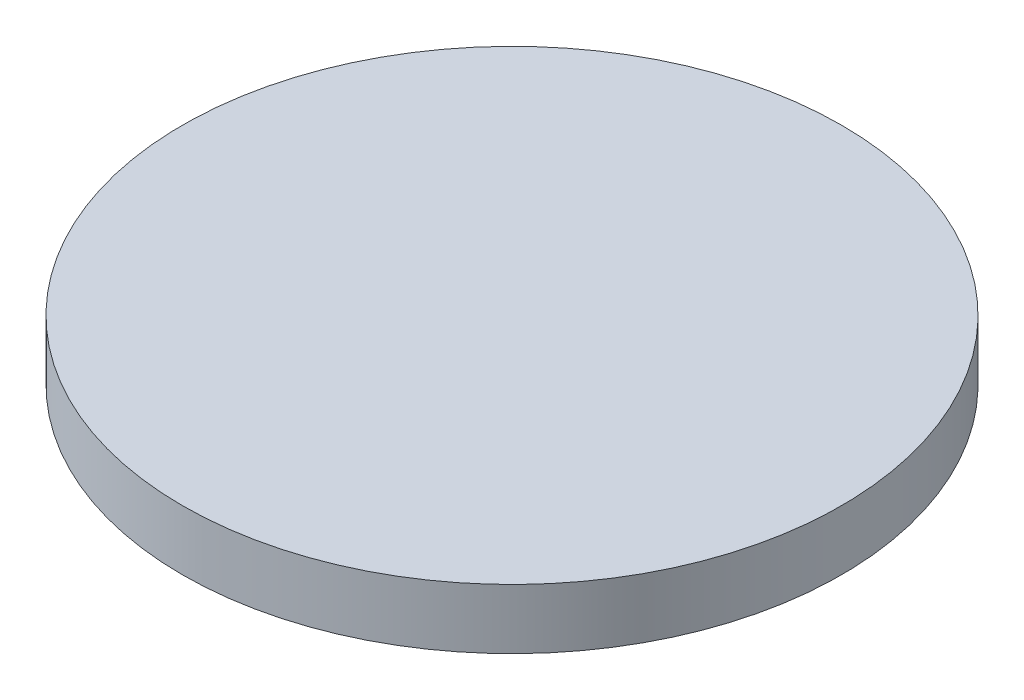
SolidWorks part; units mm, degrees
material "Natural Rubber"
ref_plane "Front Plane" through (0, 0, 0) normal (0, 0, 1) x (1, 0, 0)
ref_plane "Top Plane" through (0, 0, 0) normal (0, 1, 0) x (1, 0, 0)
ref_plane "Right Plane" through (0, 0, 0) normal (1, 0, 0) x (0, 0, -1)
sketch "BaseS" plane through (0, 0, 0) normal (0, 1, 0) x (1, 0, 0)
  circle A0 centre (0, 0) radius 2.75
  dimension "Dia" = 5.5
extrude "BASE" add sketch "BaseS" against normal blind 0.5
